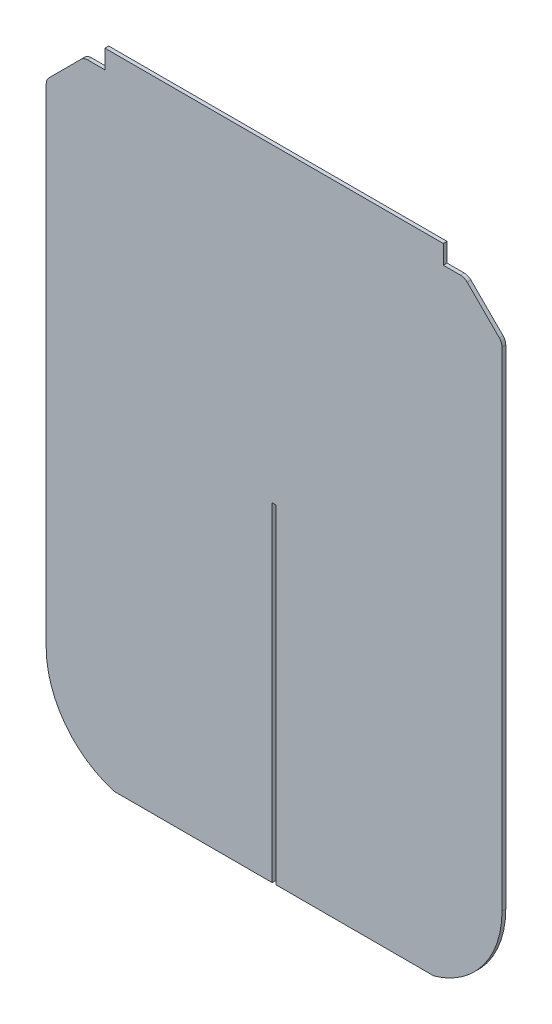
SolidWorks part; units mm, degrees
ref_plane "Front Plane" through (0, 0, 0) normal (0, 0, 1) x (1, 0, 0)
ref_plane "Top Plane" through (0, 0, 0) normal (0, 1, 0) x (1, 0, 0)
ref_plane "Right Plane" through (0, 0, 0) normal (1, 0, 0) x (0, 0, -1)
sketch "Sketch1" plane through (0, 0, 0) normal (0, 0, 1) x (1, 0, 0)
  line L0 (48.5, -48.8093) -> (48.5, 132) construction
  line L1 (14.5, 0) -> (48.1, 0)
  line L2 (0, 19.2289) -> (0, 124)
  line L3 (8, 132) -> (12.5, 132)
  line L4 (97, 19.2289) -> (97, 124)
  line L5 (12.5, 132) -> (48.5, 132) construction
  line L6 (12.5, 132) -> (12.5, 136)
  line L7 (12.5, 136) -> (45.9399, 136)
  line L8 (84.5, 132) -> (84.5, 136)
  line L9 (48.5, 132) -> (84.5, 132) construction
  line L10 (84.5, 132) -> (89, 132)
  line L11 (48.5, 132) -> (84.5, 132) construction
  line L12 (12.5, 132) -> (48.5, 132) construction
  line L13 (97, 124) -> (89, 132)
  line L14 (0, 124) -> (8, 132)
  line L15 (97, 124) -> (97, 132) construction
  line L16 (89, 132) -> (97, 132) construction
  line L17 (0, 132) -> (8, 132) construction
  line L18 (0, 124) -> (0, 132) construction
  line L19 (82.5, 0) -> (97, 0) construction
  line L20 (97, 0) -> (97, 19.2289) construction
  line L21 (0, 0) -> (14.5, 0) construction
  line L22 (0, 0) -> (0, 19.2289) construction
  line L23 (48.5, 136) -> (45.9399, 136) construction
  line L24 (45.9399, 136) -> (48.5, 136) construction
  line L26 (48.1, 70) -> (48.9, 70)
  line L28 (45.9399, 136) -> (84.5, 136)
  line L29 (48.5, 136) -> (45.9399, 136) construction
  line L30 (48.5, 132) -> (48.5, 136) construction
  line L31 (48.5, 136) -> (48.5, 206.0689) construction
  line L32 (45.9399, 136) -> (48.5, 136) construction
  line L33 (48.1, 70) -> (48.1, 0)
  line L34 (48.9, 70) -> (48.9, 0)
  line L35 (48.9, 0) -> (82.5, 0)
  arc A0 (0, 19.2289) -> (14.5, 0) centre (20, 19.2289) ccw
  arc A1 (82.5, 0) -> (97, 19.2289) centre (77, 19.2289) ccw
  arc A2 (14.5, 0) -> (0, 19.2289) centre (20, 19.2289) ccw construction
  arc A3 (97, 19.2289) -> (82.5, 0) centre (77, 19.2289) ccw construction
  point P17 (48.5, 70)
  dimension "D11" = 40
  dimension "D12" = 40
  dimension "D1" = 97
  dimension "D2" = 132
  dimension "D3" = 72
  dimension "D4" = 4
  dimension "D5" = 48.5
  dimension "D6" = 36
  dimension "D7" = 8
  dimension "D8" = 8
  dimension "D9" = 8
  dimension "D10" = 8
  dimension "D13" = 68
  dimension "D14" = 34
  dimension "D16" = 0.8
  dimension "D15" = 70
extrude "Boss-Extrude1" add sketch "Sketch1" along normal blind 0.8
fillet "Fillet1" radius 2 4 edges at (8, 132, 0.4) (0, 124, 0.4) (89, 132, 0.4) (97, 124, 0.4)
equation "\"D5@Sketch1\"=\"D1@Sketch1\"/2"
equation "\"D6@Sketch1\"=\"D3@Sketch1\"/2"
equation "\"D14@Sketch1\"=\"D13@Sketch1\"/2"
equation "\"D15@Sketch1\"=((\"D2@Sketch1\"+\"D4@Sketch1\")/2)+2"
